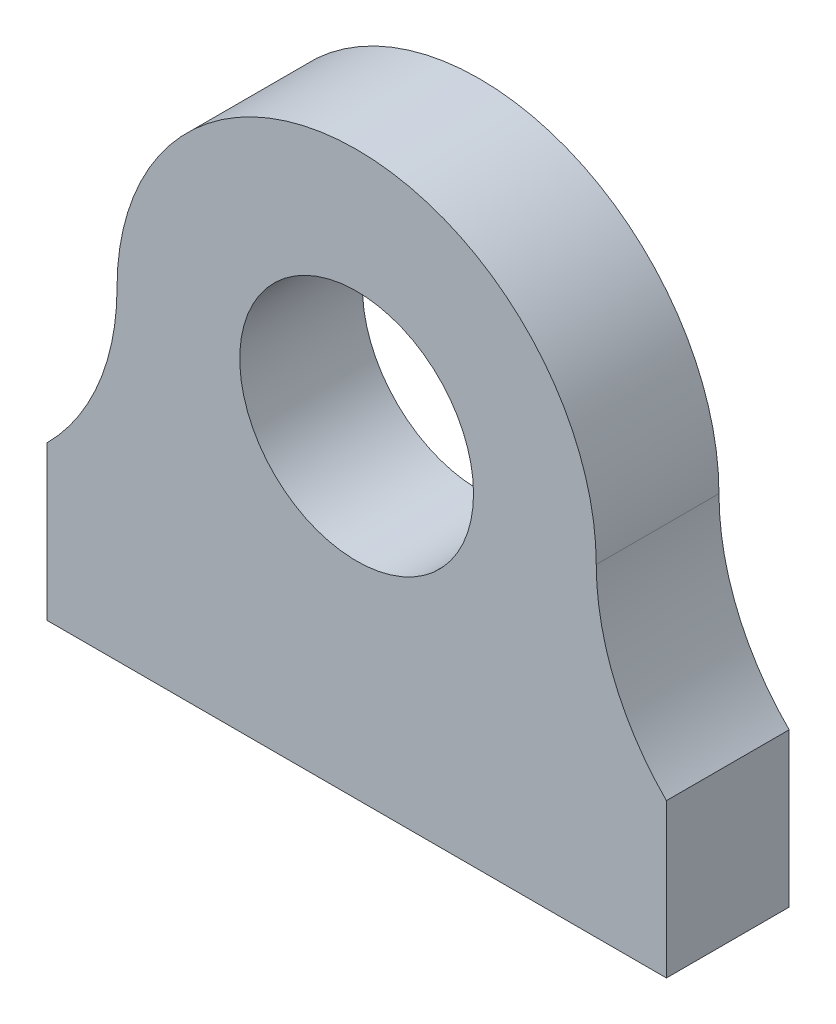
SolidWorks part; units mm, degrees
material "Hexcel AS4C (3000 Filaments)"
ref_plane "Front" through (0, 0, 0) normal (0, 0, 1) x (1, 0, 0)
ref_plane "Top" through (0, 0, 0) normal (0, 1, 0) x (1, 0, 0)
ref_plane "Right" through (0, 0, 0) normal (1, 0, 0) x (0, 0, -1)
sketch "Sketch1" plane through (0, 0, 0) normal (0, 0, 1) x (1, 0, 0)
  line L0 (-11.5992, 2.2972) -> (-11.5992, -0.5624)
  line L9 (1.0225, 9.2) -> (1.0225, 4.4375) construction
  line L12 (13.6443, 2.2972) -> (13.6443, -0.5624)
  line L13 (1.0225, -0.5624) -> (1.0225, -8.6169) construction
  line L15 (-11.5992, -0.5624) -> (-11.5992, -3.9611)
  line L16 (-11.5992, -3.9611) -> (13.6443, -3.9611)
  line L17 (13.6443, -0.5624) -> (13.6443, -3.9611)
  circle A0 centre (1.0225, 9.2) radius 4.7625
  arc A1 (10.785, 9.2) -> (-8.74, 9.2) centre (1.0225, 9.2) ccw
  arc A2 (-11.5992, 2.2972) -> (-8.74, 9.2) centre (-18.502, 9.2) ccw
  circle A3 centre (1.0225, 9.2) radius 9.7625 construction
  arc A4 (13.6443, 2.2972) -> (10.785, 9.2) centre (20.547, 9.2) cw
  dimension "D2" = 9.525
  dimension "D3" = 5
extrude "Boss-Extrude1" add sketch "Sketch1" along normal blind 5
